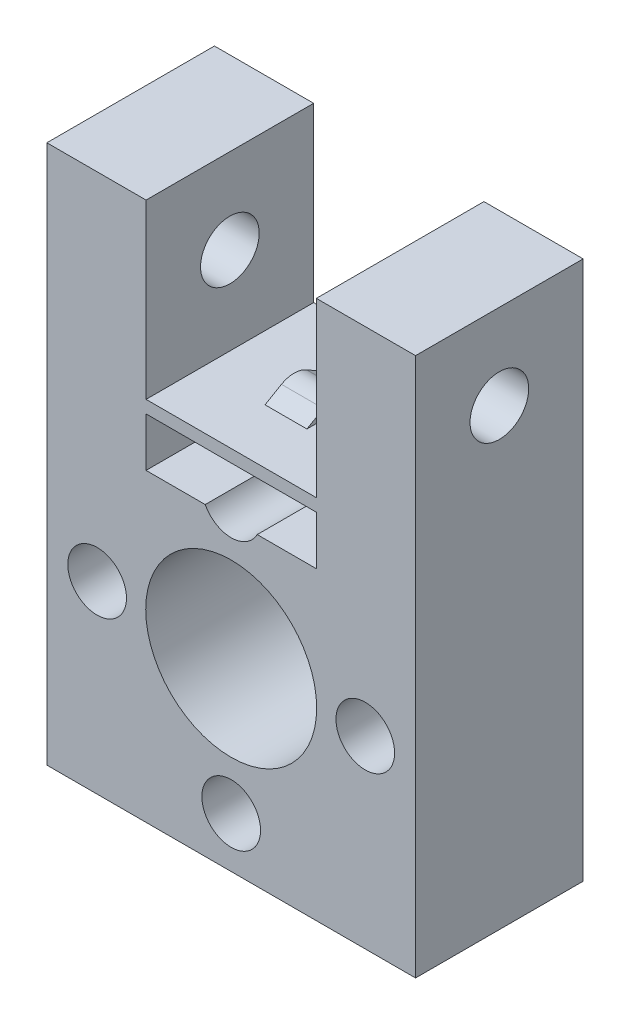
SolidWorks part; units mm, degrees
material "ABS PC"
ref_plane "Front Plane" through (0, 0, 0) normal (0, 0, 1) x (1, 0, 0)
ref_plane "Top Plane" through (0, 0, 0) normal (0, 1, 0) x (1, 0, 0)
ref_plane "Right Plane" through (0, 0, 0) normal (1, 0, 0) x (0, 0, -1)
sketch "Sketch1" plane through (0, 0, 0) normal (0, 0, 1) x (1, 0, 0)
  circle A0 centre (0, 0) radius 5.1
  circle A1 centre (0, 0) radius 11
  dimension "D1" = 22
  dimension "D2" = 10.2
extrude "Boss-Extrude1" add sketch "Sketch1" along normal blind 10
sketch "Sketch2" plane through (0, 0, 10) normal (0, 0, 1) x (1, 0, 0)
  circle A0 centre (0, 8) radius 1.75
  circle A1 centre (0, 0) radius 11
  circle A2 centre (0, 0) radius 11
  circle A3 centre (0, 0) radius 11
  circle A4 centre (8, 0) radius 1.75
  circle A5 centre (0, 0) radius 11
  circle A6 centre (0, -8) radius 1.75
  circle A7 centre (0, 0) radius 11
  circle A8 centre (-8, 0) radius 1.75
  point P17 (0, 0)
  dimension "D2" = 3.5
  dimension "D3" = 8
  dimension "D1" = 0
  dimension "D4" = 4
extrude "Cut-Extrude1" cut sketch "Sketch2" against normal through all contours A0 | A8 | A4 | A6
sketch "Sketch3" plane through (0, 0, 0) normal (0, 1, 0) x (1, 0, 0)
  line L1 (-11, 0) -> (11, 0)
  line L2 (-11, 0) -> (-11, -10)
  line L3 (-11, -10) -> (11, -10)
  line L4 (11, 0) -> (11, -10)
extrude "Boss-Extrude2" add sketch "Sketch3" along normal blind 10.16 from offset 11 separate body contours L2 L1 L4 L3
sketch "Sketch5" plane through (0, 11, 0) normal (0, -1, 0) x (1, 0, 0)
  line L4 (11, 10) -> (-11, 10)
  line L5 (-11, 10) -> (-11, 0)
  line L6 (-11, 0) -> (11, 0)
  line L7 (11, 0) -> (11, 10)
  line L8 (11, 10) -> (-11, 10)
  line L9 (-11, 10) -> (-11, 0)
  line L10 (-11, 0) -> (11, 0)
  line L11 (11, 0) -> (11, 10)
  dimension "D1" = 0
extrude "Boss-Extrude3" add sketch "Sketch5" along normal up to surface (11 mm away)
sketch "Sketch6" plane through (0, 0, 10) normal (0, 0, 1) x (1, 0, 0)
  line L0 (-11, 21.16) -> (11, 21.16) construction
  line L1 (-5.08, 21.16) -> (5.08, 21.16)
  line L2 (-5.08, 21.16) -> (-5.08, 7.19)
  line L3 (-5.08, 7.19) -> (5.08, 7.19)
  line L4 (5.08, 21.16) -> (5.08, 7.19)
  point P6 (0, 21.16)
  point P7 (0, 21.16)
  dimension "D1" = 10.16
  dimension "D2" = 13.97
extrude "Cut-Extrude2" cut sketch "Sketch6" against normal through all
sketch "Sketch7" plane through (11, 0, 0) normal (1, 0, 0) x (0, 0, -1)
  line L0 (-10, 14.796) -> (0, 14.796) construction
  line L1 (-10, 21.16) -> (-10, 0) construction
  line L2 (0, 21.16) -> (0, 0) construction
  line L3 (0, 21.16) -> (-10, 21.16) construction
  circle A0 centre (-5, 16.08) radius 1.75
  point P10 (-5, 14.796)
  dimension "D1" = 3.5
  dimension "D2" = 6.364
  dimension "D3" = 5.08
extrude "Cut-Extrude3" cut sketch "Sketch7" against normal through all
sketch "Sketch8" plane through (0, 0, 10) normal (0, 0, 1) x (1, 0, 0)
  line L1 (-11, -11) -> (11, -11)
  line L2 (-11, -11) -> (-11, 0)
  line L3 (-11, 0) -> (11, 0)
  line L4 (11, -11) -> (11, 0)
  line L7 (-5.08, 7.19) -> (-5.08, 21.16)
  line L8 (-5.08, 21.16) -> (-11, 21.16)
  line L9 (-11, 21.16) -> (-11, 0)
  line L10 (11, 0) -> (11, 21.16)
  line L11 (11, 21.16) -> (5.08, 21.16)
  line L12 (5.08, 21.16) -> (5.08, 7.19)
  line L13 (5.08, 7.19) -> (1.5513, 7.19)
  line L14 (-5.08, 7.19) -> (-5.08, 21.16)
  line L15 (-5.08, 21.16) -> (-11, 21.16)
  line L16 (-11, 21.16) -> (-11, 0)
  line L17 (11, 0) -> (11, 21.16)
  line L18 (11, 21.16) -> (5.08, 21.16)
  line L19 (5.08, 21.16) -> (5.08, 7.19)
  line L20 (5.08, 7.19) -> (1.5513, 7.19)
  line L26 (-1.5513, 7.19) -> (-5.08, 7.19)
  line L27 (-1.5513, 7.19) -> (-5.08, 7.19)
  arc A1 (-11, 0) -> (11, 0) centre (0, 0) ccw
  arc A2 (-11, 0) -> (11, 0) centre (0, 0) ccw
  arc A4 (-1.5513, 7.19) -> (1.5513, 7.19) centre (0, 8) ccw
  arc A5 (-1.5513, 7.19) -> (1.5513, 7.19) centre (0, 8) ccw
  arc M16 (-11, 0) -> (11, 0) centre (0, 0) ccw
  dimension "D1" = 0
extrude "Boss-Extrude4" add sketch "Sketch8" along direction (0, 0, 1) on the side against the normal through all contours L2 L1 M16 | L1 L4 M16
ref_plane "Plane1" through (0, 0, 0) normal (-1, 0, 0) x (0, 0, 1)
sketch "Sketch9" plane through (0, 0, 0) normal (-1, 0, 0) x (0, 0, 1)
  line L0 (0, -11) -> (0, 21.16) construction
  line L1 (0, 10.86) -> (10, 10.86)
  line L2 (0, 10.86) -> (0, 10.11)
  line L3 (0, 10.11) -> (10, 10.11)
  line L4 (10, 10.86) -> (10, 10.11)
  line L5 (10, -11) -> (10, 21.16) construction
  line L6 (0, 21.16) -> (10, 21.16) construction
  line L7 (3.2679, 10.86) -> (5, 11.86)
  line L8 (5, 11.86) -> (6.7321, 10.86)
  point P13 (5, 10.86)
  dimension "D1" = 10.3
  dimension "D2" = 0.75
  dimension "D3" = 0
  dimension "D4" = 30
  dimension "D5" = 30
  dimension "D6" = 2
extrude "Boss-Extrude5" add sketch "Sketch9" along normal through all and the other way through all contours L2 L1 L4 L3
sketch "Sketch10" plane through (0, 0, 0) normal (-1, 0, 0) x (0, 0, 1)
  line L0 (0, 10.86) -> (10, 10.86) construction
  line L1 (0, 10.86) -> (10, 10.86)
  line L2 (3.2679, 10.86) -> (5, 11.86)
  line L3 (5, 11.86) -> (6.7321, 10.86)
  line L4 (10, -11) -> (10, 21.16) construction
  point P9 (0.6925, 12.3098)
  dimension "D1" = 30
  dimension "D2" = 2
  dimension "D3" = 2
  dimension "D4" = 5
extrude "Boss-Extrude6" add sketch "Sketch10" along normal mid plane 2.5 contours L3 L2 L1
fillet "Fillet1" radius 1.5 1 edges at (0, 11.86, 5)
